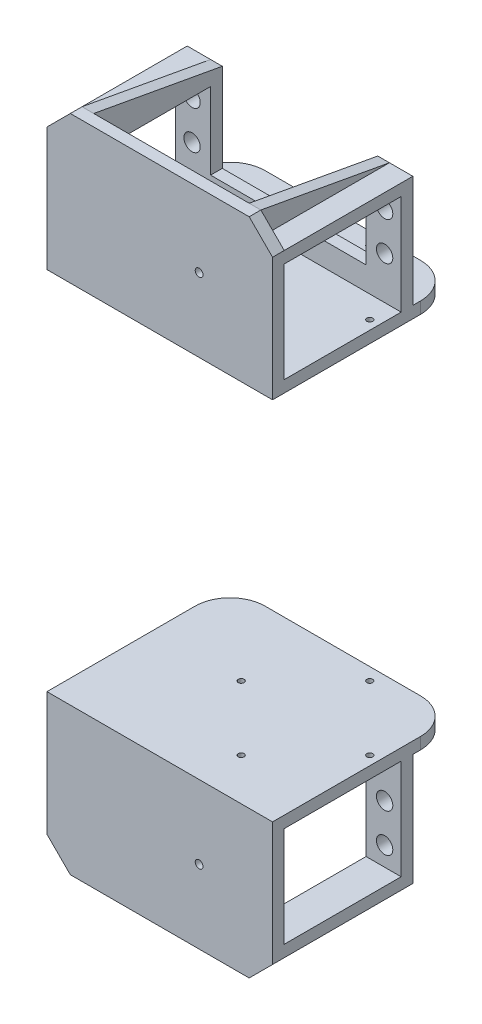
SolidWorks part; units mm, degrees
ref_plane "前视基准面" through (0, 0, 0) normal (0, 0, 1) x (1, 0, 0)
ref_plane "上视基准面" through (0, 0, 0) normal (0, 1, 0) x (1, 0, 0)
ref_plane "右视基准面" through (0, 0, 0) normal (1, 0, 0) x (0, 0, -1)
sketch "草图1" plane through (0, 0, 0) normal (0, 0, 1) x (1, 0, 0)
  line L0 (-4.8606, 17.287) -> (-4.8606, -2.413) construction
  line L1 (-14.7106, 17.287) -> (25.1894, 17.287)
  line L2 (-14.7106, 17.287) -> (-14.7106, -2.413)
  line L3 (-14.7106, -2.413) -> (25.1894, -2.413)
  line L4 (25.1894, 17.287) -> (25.1894, -2.413)
  line L5 (-23.7106, 26.287) -> (34.1894, 26.287)
  line L6 (-23.7106, 26.287) -> (-23.7106, -11.413)
  line L7 (-23.7106, -11.413) -> (34.1894, -11.413)
  line L8 (34.1894, 26.287) -> (34.1894, -11.413)
  line L9 (-14.7106, 7.437) -> (-4.8606, 7.437) construction
  line L10 (-14.7106, 17.287) -> (-23.7106, 17.287) construction
  line L12 (-14.7106, -2.413) -> (-23.7106, -2.413) construction
  line L14 (-14.7106, 17.287) -> (-14.7106, 26.287) construction
  line L16 (25.1894, 17.287) -> (25.1894, 26.287) construction
  circle A0 centre (-19.4706, 12.357) radius 2.1
  circle A1 centre (-19.4706, 2.517) radius 2.1
  circle A2 centre (29.9494, 12.357) radius 2.1
  circle A3 centre (29.9494, 2.517) radius 2.1
  dimension "D7" = 4.2
  dimension "D9" = 4.93
  dimension "D10" = 4.2
  dimension "D11" = 4.93
  dimension "D12" = 4.76
  dimension "D13" = 4.2
  dimension "D14" = 4.2
  dimension "D17" = 4.76
  dimension "D1" = 39.9
  dimension "D2" = 19.7
  dimension "D3" = 9
  dimension "D4" = 9
  dimension "D5" = 9
  dimension "D6" = 9
  dimension "D8" = 4.76
  dimension "D15" = 4.93
  dimension "D16" = 4.93
  dimension "D18" = 4.76
  dimension "D19" = 9.85
  dimension "D20" = 9.85
extrude "凸台-拉伸1" add sketch "草图1" along normal blind 3
sketch "草图2" plane through (0, 0, 3) normal (0, 0, 1) x (1, 0, 0)
  line L5 (-14.7106, 17.287) -> (-14.7106, 26.287) construction
  line L6 (-14.7106, 17.287) -> (-14.7106, -2.413) construction
  line L7 (25.1894, 17.287) -> (25.1894, 26.287) construction
  line L8 (34.1894, -11.413) -> (34.1894, 26.287) construction
  line L13 (-23.7106, 26.287) -> (34.1894, 26.287)
  line L14 (-23.7106, 26.287) -> (-23.7106, 23.287)
  line L15 (-23.7106, 23.287) -> (34.1894, 23.287)
  line L16 (34.1894, 26.287) -> (34.1894, 23.287)
extrude "凸台-拉伸2" add sketch "草图2" along normal blind 30
sketch "草图3" plane through (0, 0, 33) normal (0, 0, 1) x (1, 0, 0)
  line L0 (-14.7106, -2.413) -> (-14.7106, 31.6525) construction
  line L1 (25.1894, -2.413) -> (25.1894, 31.6525) construction
  line L2 (-14.7106, -2.413) -> (25.1894, -2.413) construction
  line L3 (-4.8606, -2.413) -> (-4.8606, 17.287) construction
  line L4 (25.1894, 17.287) -> (-14.7106, 17.287) construction
  line L5 (-4.8606, 17.287) -> (-4.8606, 7.437) construction
  line L6 (-4.8606, 7.437) -> (-14.7106, 7.437) construction
  line L7 (-14.7106, 26.287) -> (-23.7106, 26.287)
  line L8 (-14.7106, 26.287) -> (25.1894, 26.287)
  line L12 (-23.7106, 26.287) -> (-23.7106, -2.413)
  line L13 (-23.7106, 23.287) -> (-23.7106, -11.413) construction
  line L15 (25.1894, 26.287) -> (34.1894, 26.287)
  line L16 (34.1894, 26.287) -> (34.1894, -2.413)
  line L17 (34.1894, -11.413) -> (34.1894, 23.287) construction
  line L19 (34.1894, -2.413) -> (34.1894, -5.413)
  line L20 (34.1894, -5.413) -> (-23.7106, -5.413)
  line L21 (-23.7106, -5.413) -> (-23.7106, -2.413)
  circle A1 centre (15.3394, 7.437) radius 1
  dimension "D5" = 9.85
  dimension "D6" = 2
  dimension "D1" = 9.85
  dimension "D2" = 9.85
  dimension "D4" = 3
extrude "凸台-拉伸3" add sketch "草图3" along normal blind 3
sketch "草图9" plane through (0, 0, 0) normal (0, 0, -1) x (-1, 0, 0)
  line L0 (23.7106, 26.287) -> (23.7106, -11.413) construction
  line L1 (-34.1894, 26.287) -> (23.7106, 26.287)
  line L2 (-34.1894, 26.287) -> (-34.1894, 23.287)
  line L3 (-34.1894, 23.287) -> (23.7106, 23.287)
  line L4 (23.7106, 26.287) -> (23.7106, 23.287)
  dimension "D1" = 3
extrude "凸台-拉伸4" add sketch "草图9" along normal blind 11
sketch "草图10" plane through (0, 26.287, 0) normal (0, 1, 0) x (1, 0, 0)
  line L0 (34.1894, -36) -> (34.1894, 11) construction
  line L1 (34.1894, -36) -> (-23.7106, -36) construction
  line L2 (-23.7106, 2) -> (-23.7106, 11)
  line L3 (-23.7106, 11) -> (-14.7106, 11) construction
  line L4 (-23.7106, 11) -> (-23.7106, 2) construction
  line L5 (-23.7106, 2) -> (-14.7106, 2) construction
  line L6 (-14.7106, 11) -> (-14.7106, 2) construction
  line L7 (34.1894, 11) -> (25.1894, 11) construction
  line L8 (34.1894, 11) -> (34.1894, 2) construction
  line L9 (34.1894, 2) -> (25.1894, 2) construction
  line L10 (25.1894, 11) -> (25.1894, 2) construction
  line L11 (-23.7106, 11) -> (-14.7106, 11)
  line L12 (25.1894, 11) -> (34.1894, 11)
  line L13 (34.1894, 11) -> (34.1894, 2)
  line L15 (15.3394, 9.3) -> (15.3394, -26.7) construction
  line L17 (33.3394, -8.7) -> (-2.6606, -8.7) construction
  circle A0 centre (15.3394, -8.7) radius 18 construction
  arc A1 (-23.7106, 2) -> (-14.7106, 11) centre (-14.7106, 2) cw
  arc A2 (25.1894, 11) -> (34.1894, 2) centre (25.1894, 2) cw
  circle A3 centre (15.3394, 7.8) radius 0.75
  circle A5 centre (31.8394, -8.7) radius 0.75
  circle A6 centre (15.3394, -25.2) radius 0.75
  circle A7 centre (-1.1606, -8.7) radius 0.75
  dimension "D1" = 36
  dimension "D2" = 18.85
  dimension "D3" = 27.3
  dimension "D8" = 1.5
  dimension "D9" = 1.5
  dimension "D11" = 1.5
  dimension "D13" = 1.5
  dimension "D14" = 1.5
  dimension "D4" = 9
  dimension "D5" = 9
  dimension "D6" = 9
  dimension "D7" = 9
  dimension "D10" = 1.5
  dimension "D12" = 1.5
  dimension "D15" = 1.5
  dimension "D24" = 0.85
  dimension "D25" = 2.35
extrude "切除-拉伸3" cut sketch "草图10" against normal blind 3
ref_plane "基准面1" through (0, 73.187, 0) normal (0, 1, 0) x (1, 0, 0)
mirror "镜向1" about plane through (0, 73.187, 0) normal (0, 1, 0) of bodies 113
sketch "草图11" plane through (0, 0, 33) normal (0, 0, -1) x (-1, 0, 0)
  line L0 (-34.1894, -11.413) -> (-34.1894, 23.287) construction
  line L1 (14.7106, -2.413) -> (23.7106, -2.413)
  line L2 (14.7106, -2.413) -> (14.7106, -5.413)
  line L3 (14.7106, -5.413) -> (23.7106, -5.413)
  line L4 (23.7106, -2.413) -> (23.7106, -5.413)
  line L5 (-25.1894, -2.413) -> (-34.1894, -2.413)
  line L6 (-25.1894, -2.413) -> (-25.1894, -5.413)
  line L7 (-25.1894, -5.413) -> (-34.1894, -5.413)
  line L8 (-34.1894, -2.413) -> (-34.1894, -5.413)
extrude "凸台-拉伸5" add sketch "草图11" along normal blind 32
sketch "草图12" plane through (0, 0, 0) normal (0, 0, -1) x (-1, 0, 0)
  line L0 (-25.1894, -2.413) -> (-25.1894, -5.413)
  line L1 (-25.1894, -5.413) -> (-34.1894, -5.413)
  line L2 (-34.1894, -11.413) -> (-34.1894, 23.287) construction
  line L3 (-34.1894, -5.413) -> (-34.1894, -11.413)
  line L4 (-34.1894, -11.413) -> (23.7106, -11.413)
  line L5 (23.7106, -11.413) -> (23.7106, -5.413)
  line L6 (23.7106, 23.287) -> (23.7106, -11.413) construction
  line L7 (23.7106, -5.413) -> (14.7106, -5.413)
  line L8 (14.7106, -5.413) -> (14.7106, -2.413)
  line L9 (14.7106, -2.413) -> (-25.1894, -2.413)
  dimension "D1" = 3
  dimension "D2" = 3
extrude "切除-拉伸4" cut sketch "草图12" against normal blind 9
sketch "草图13" plane through (0, 0, 36) normal (0, 0, 1) x (1, 0, 0)
  line L0 (-23.7106, -5.413) -> (34.1894, -5.413)
  line L1 (34.1894, -5.413) -> (28.1894, -11.413)
  line L2 (28.1894, -11.413) -> (-17.7106, -11.413)
  line L3 (-17.7106, -11.413) -> (-23.7106, -5.413)
  line L4 (-23.7106, 26.287) -> (-23.7106, -5.413) construction
  line L5 (34.1894, -5.413) -> (34.1894, 26.287) construction
  dimension "D1" = 6
  dimension "D2" = 6
  dimension "D3" = 6
extrude "凸台-拉伸6" add sketch "草图13" against normal blind 3
sketch "草图17" plane through (0, -5.413, 0) normal (0, -1, 0) x (1, 0, 0)
  line L1 (-17.7106, 33) -> (-14.7106, 33)
  line L2 (-17.7106, 33) -> (-17.7106, 0)
  line L3 (-17.7106, 0) -> (-14.7106, 0)
  line L4 (-14.7106, 33) -> (-14.7106, 0)
  line L6 (28.1894, 33) -> (25.1894, 33)
  line L7 (28.1894, 33) -> (28.1894, 0)
  line L8 (28.1894, 0) -> (25.1894, 0)
  line L9 (25.1894, 33) -> (25.1894, 0)
extrude "凸台-拉伸7" add sketch "草图17" along normal blind 6
sketch "草图19" plane through (-17.7106, 0, 0) normal (-1, 0, 0) x (0, 0, 1)
  line L0 (0, -5.413) -> (0, -11.413)
  line L1 (0, -11.413) -> (33, -11.413)
  line L2 (33, -11.413) -> (0, -5.413)
extrude "切除-拉伸5" cut sketch "草图19" against normal blind 52
delete or keep bodies "实体-删除/保留 1" type delete bodies bodies 114
mirror "镜向2" about plane through (0, 73.187, 0) normal (0, 1, 0) of bodies 119
